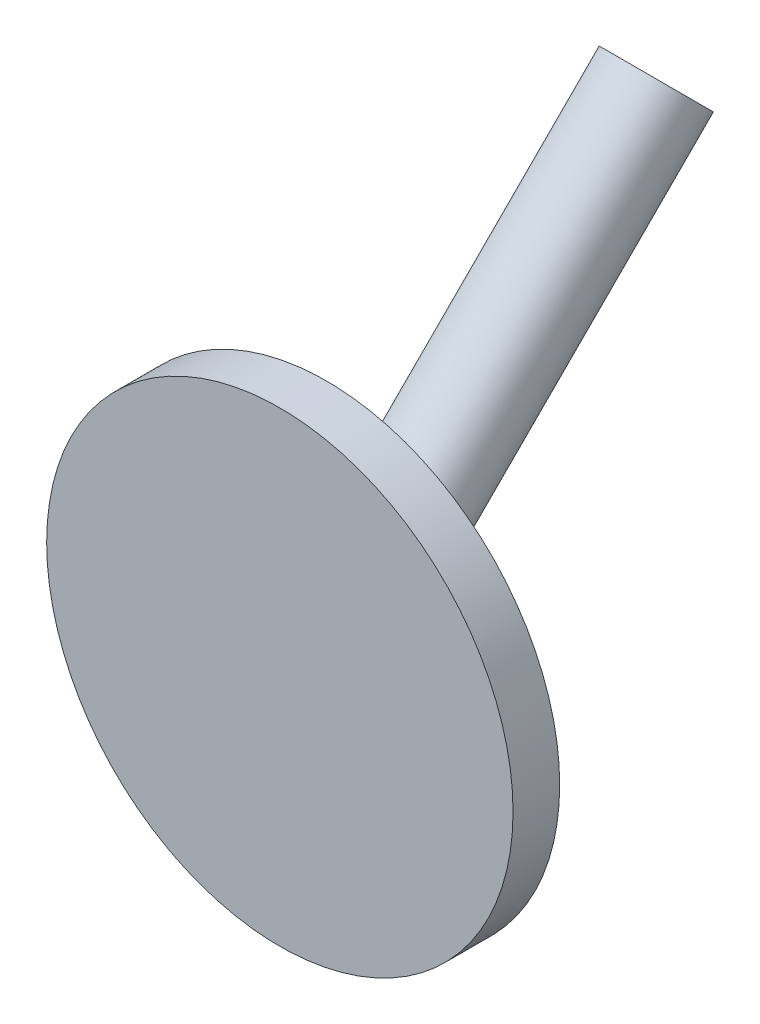
SolidWorks part; units mm, degrees
material "Glass"
ref_plane "Front Plane" through (0, 0, 0) normal (0, 0, 1) x (1, 0, 0)
ref_plane "Top Plane" through (0, 0, 0) normal (0, 1, 0) x (1, 0, 0)
ref_plane "Right Plane" through (0, 0, 0) normal (1, 0, 0) x (0, 0, -1)
sketch "Sketch1" plane through (0, 0, 0) normal (0, 0, 1) x (1, 0, 0)
  circle A0 centre (0, 0) radius 10
  dimension "D1" = 20
extrude "Boss-Extrude1" add sketch "Sketch1" along normal blind 2
sketch "Sketch2" plane through (0, 0, 0) normal (1, 0, 0) x (0, 0, -1)
  line L0 (0, 0) -> (45.2676, 45.2676) construction
  line L1 (0, 0) -> (13.6656, 0) construction
  line L2 (0, 0) -> (76.3646, -76.3646) construction
  dimension "D1" = 45
  dimension "D2" = 45
ref_plane "Plane1" through (0, 0, 0) normal (0, 0.7071, -0.7071) x (-1, 0, 0)
ref_plane "Plane2" through (0, 0, 0) normal (0, -0.7071, -0.7071) x (-1, 0, 0)
sketch "Sketch3" plane through (0, 0, 0) normal (0, -0.7071, -0.7071) x (-1, 0, 0)
  circle A0 centre (0, 0) radius 2
  dimension "D1" = 4
extrude "Boss-Extrude2" add sketch "Sketch3" along normal blind 10
sketch "Sketch4" plane through (0, 0, 0) normal (0, 0.7071, -0.7071) x (-1, 0, 0)
  circle A0 centre (0, 0) radius 2
  dimension "D1" = 4
extrude "Boss-Extrude3" add sketch "Sketch4" along normal blind 20
